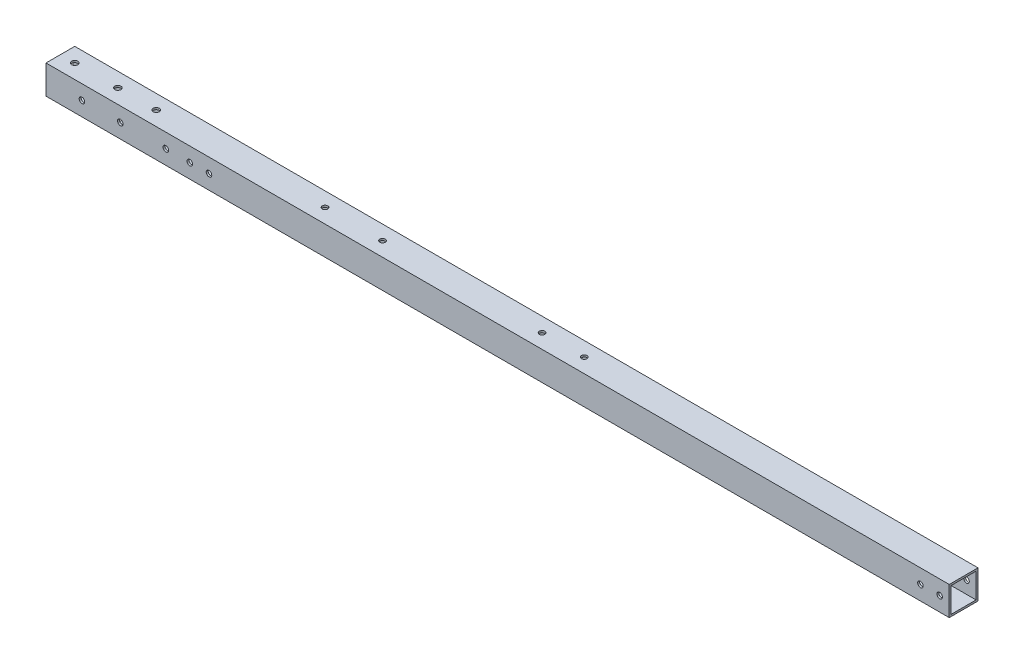
SolidWorks part; units mm, degrees
material "Thornel Mat VMA"
ref_plane "前视基准面" through (0, 0, 0) normal (0, 0, 1) x (1, 0, 0)
ref_plane "上视基准面" through (0, 0, 0) normal (0, 1, 0) x (1, 0, 0)
ref_plane "右视基准面" through (0, 0, 0) normal (1, 0, 0) x (0, 0, -1)
other "Configuration Table"
sketch "草图1" plane through (0, 0, 0) normal (0, 1, 0) x (1, 0, 0)
  line L0 (-235.5, 0) -> (235.5, 0)
  dimension "D1" = 471
other "铝管 15X15X1(1)"
ref_plane "基准面1" through (-235.5, 0, 0) normal (1, 0, 0) x (0, 0, -1)
sketch "草图11" plane through (-235.5, 0, 0) normal (1, 0, 0) x (0, 0, -1)
  line L1 (-7.5, -7.5) -> (7.5, -7.5)
  line L2 (-7.5, -7.5) -> (-7.5, 7.5)
  line L3 (-7.5, 7.5) -> (7.5, 7.5)
  line L4 (7.5, -7.5) -> (7.5, 7.5)
  line L5 (-7.5, -7.5) -> (7.5, 7.5) construction
  line L6 (-7.5, 7.5) -> (7.5, -7.5) construction
  line L7 (-6.5, -6.5) -> (6.5, -6.5)
  line L8 (-6.5, -6.5) -> (-6.5, 6.5)
  line L9 (-6.5, 6.5) -> (6.5, 6.5)
  line L10 (6.5, -6.5) -> (6.5, 6.5)
  line L11 (-6.5, -6.5) -> (6.5, 6.5) construction
  line L12 (-6.5, 6.5) -> (6.5, -6.5) construction
  point P0 (0, 0)
  point P6 (0, 0)
  point P11 (0, 0)
  dimension "D1" = 15
  dimension "D2" = 15
  dimension "D3" = 13
  dimension "D4" = 13
sketch "草图12" plane through (0, 7.5, 0) normal (0, 1, 0) x (1, 0, 0)
  line L0 (-235.5, 0) -> (235.5, 0) construction
  line L1 (-235.5, 7.5) -> (-235.5, -7.5) construction
  circle A0 centre (-205.5, 0) radius 1.6
  circle A1 centre (-185.5, 0) radius 1.6
  circle A2 centre (-228, 0) radius 1.6
  dimension "D1" = 3.2
  dimension "D2" = 22.5
  dimension "D3" = 3.2
  dimension "D4" = 20
  dimension "D5" = 3.2
  dimension "D6" = 7.5
extrude "切除-拉伸1" cut sketch "草图12" against normal through all
sketch "草图13" plane through (0, 7.5, 0) normal (0, 1, 0) x (1, 0, 0)
  line L0 (-82.5, 7.5) -> (-82.5, -7.5) construction
  line L1 (235.5, 7.5) -> (-235.5, 7.5) construction
  line L2 (235.5, -7.5) -> (-235.5, -7.5) construction
  line L3 (-235.5, 0) -> (235.5, 0) construction
  line L5 (235.5, 7.5) -> (235.5, -7.5) construction
  line L6 (-7.5, 7.5) -> (-7.5, -7.5) construction
  circle A0 centre (-97.5, 0) radius 1.45
  circle A1 centre (-67.5, 0) radius 1.45
  circle A2 centre (-82.5, -42.5) radius 60 construction
  circle A3 centre (-7.5, -25.0644) radius 17 construction
  dimension "D1" = 2.9
  dimension "D2" = 2.9
  dimension "D3" = 15
  dimension "D4" = 15
  dimension "D6" = 120
  dimension "D8" = 34
  dimension "D5" = 318
  dimension "D7" = 35
  dimension "D9" = 75
  dimension "D10" = 75
extrude "切除-拉伸2" cut sketch "草图13" against normal through all
sketch "草图14" plane through (0, 0, -7.5) normal (0, 0, -1) x (-1, 0, 0)
  line L0 (235.5, 0) -> (-235.5, 0) construction
  line L1 (235.5, -7.5) -> (235.5, 7.5) construction
  circle A0 centre (216.75, 0) radius 1.45
  circle A1 centre (196.75, 0) radius 1.45
  dimension "D1" = 2.9
  dimension "D2" = 2.9
  dimension "D3" = 18.75
  dimension "D4" = 20
extrude "切除-拉伸3" cut sketch "草图14" against normal through all
sketch "草图15" plane through (0, 0, -7.5) normal (0, 0, -1) x (-1, 0, 0)
  line L0 (235.5, 0) -> (-235.5, 0) construction
  circle A0 centre (173, 0) radius 1.45
  circle A1 centre (160.5, 0) radius 1.45
  circle A2 centre (150.5, 0) radius 1.45
  dimension "D1" = 2.9
  dimension "D2" = 2.9
  dimension "D3" = 2.9
  dimension "D4" = 62.5
  dimension "D5" = 12.5
  dimension "D6" = 10
extrude "切除-拉伸4" cut sketch "草图15" against normal through all
sketch "草图16" plane through (0, 0, -7.5) normal (0, 0, -1) x (-1, 0, 0)
  line L0 (235.5, 0) -> (-235.5, 0) construction
  line L1 (-235.5, -7.5) -> (-235.5, 7.5) construction
  circle A0 centre (-230.5, 0) radius 1.45
  circle A1 centre (-220.5, 0) radius 1.45
  dimension "D1" = 2.9
  dimension "D2" = 2.9
  dimension "D4" = 10
  dimension "D3" = 5
extrude "切除-拉伸5" cut sketch "草图16" against normal through all
sketch "草图17" plane through (0, 7.5, 0) normal (0, 1, 0) x (1, 0, 0)
sketch "草图18" plane through (0, -7.5, 0) normal (0, -1, 0) x (1, 0, 0)
  line L0 (26.7, 7.5) -> (26.7, -7.5) construction
  line L1 (235.5, 7.5) -> (-235.5, 7.5) construction
  line L2 (235.5, -7.5) -> (-235.5, -7.5) construction
  line L3 (-235.5, 0) -> (235.5, 0) construction
  line L4 (21, 22.581) -> (21, 15.8816) construction
  line L5 (235.5, 7.5) -> (235.5, -7.5) construction
  circle A0 centre (15.7, 0) radius 1.45
  circle A1 centre (37.7, 0) radius 1.45
  dimension "D1" = 2.9
  dimension "D2" = 2.9
  dimension "D3" = 11
  dimension "D4" = 11
  dimension "D5" = 5.7
  dimension "D6" = 214.5
extrude "切除-拉伸7" cut sketch "草图18" against normal through all
